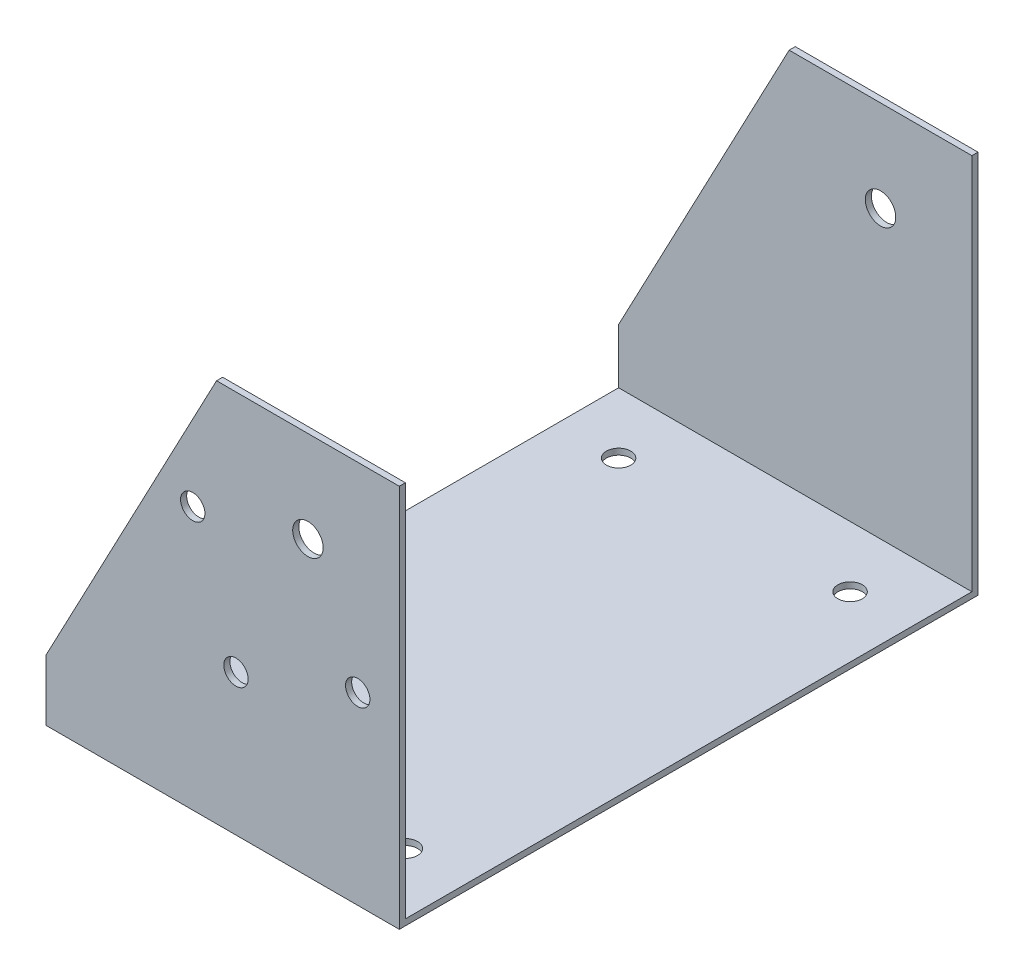
SolidWorks part; units mm, degrees
ref_plane "Alzado" through (0, 0, 0) normal (0, 0, 1) x (1, 0, 0)
ref_plane "Planta" through (0, 0, 0) normal (0, 1, 0) x (1, 0, 0)
ref_plane "Vista lateral" through (0, 0, 0) normal (1, 0, 0) x (0, 0, -1)
sketch "Croquis1" plane through (0, 0, 0) normal (0, 1, 0) x (1, 0, 0)
  line L1 (29, -47.5) -> (-29, -47.5)
  line L2 (29, -47.5) -> (29, 47.5)
  line L3 (29, 47.5) -> (-29, 47.5)
  line L4 (-29, -47.5) -> (-29, 47.5)
  line L5 (29, -47.5) -> (-29, 47.5) construction
  line L6 (29, 47.5) -> (-29, -47.5) construction
  point P0 (0, 0)
extrude "Saliente-Extruir4" add sketch "Croquis1" along normal blind 1
sketch "Croquis3" plane through (0, 0, 47.5) normal (0, 0, 1) x (1, 0, 0)
  line L0 (-29, 1) -> (29, 1)
  line L1 (29, 1) -> (29, 63)
  line L2 (29, 63) -> (-29, 63)
  line L3 (-29, 63) -> (-29, 1)
extrude "Saliente-Extruir5" add sketch "Croquis3" against normal blind 1
sketch "Croquis4" plane through (0, 0, -47.5) normal (0, 0, -1) x (-1, 0, 0)
  line L0 (-29, 1) -> (29, 1)
  line L1 (29, 1) -> (29, 63)
  line L2 (29, 63) -> (29, 1) construction
  line L3 (29, 63) -> (-29, 63)
  line L4 (-29, 63) -> (-29, 1)
extrude "Saliente-Extruir6" add sketch "Croquis4" against normal blind 1
sketch "Croquis6" plane through (0, 0, -47.5) normal (0, 0, -1) x (-1, 0, 0)
  line L0 (29, 0) -> (29, 10) construction
  line L1 (29, 63) -> (29, 0) construction
  line L2 (-29, 63) -> (1, 63) construction
  line L3 (29, 63) -> (-29, 63) construction
  line L4 (1, 63) -> (29, 10)
  line L5 (29, 10) -> (29, 63)
  line L6 (29, 63) -> (1, 63)
extrude "Cortar-Extruir4" cut sketch "Croquis6" against normal blind 1
sketch "Croquis7" plane through (0, 0, 47.5) normal (0, 0, 1) x (1, 0, 0)
  line L0 (-29, 0) -> (-29, 10) construction
  line L1 (-29, 63) -> (-29, 0) construction
  line L2 (29, 63) -> (-1, 63) construction
  line L3 (29, 63) -> (-29, 63) construction
  line L4 (-1, 63) -> (-29, 10)
  line L5 (-29, 10) -> (-29, 63)
  line L6 (-29, 63) -> (-1, 63)
extrude "Cortar-Extruir5" cut sketch "Croquis7" against normal blind 1
sketch "Croquis8" plane through (0, 0, 47.5) normal (0, 0, 1) x (1, 0, 0)
  line L0 (14, 63) -> (14, 48) construction
  line L1 (29, 63) -> (-1, 63) construction
  circle A0 centre (14, 48) radius 2.5
extrude "Cortar-Extruir6" cut sketch "Croquis8" against normal blind 1
sketch "Croquis9" plane through (0, 0, -47.5) normal (0, 0, -1) x (-1, 0, 0)
  line L0 (-14, 63) -> (-14, 48) construction
  line L1 (1, 63) -> (-29, 63) construction
  circle A0 centre (-14, 48) radius 2.5
extrude "Cortar-Extruir7" cut sketch "Croquis9" against normal blind 1
sketch "Croquis10" plane through (0, 0, 47.5) normal (0, 0, 1) x (1, 0, 0)
  line L0 (14, 50.5) -> (14, 35.5) construction
  line L3 (14, 48) -> (8.6295, 36.7125) construction
  line L4 (8.6295, 36.7125) -> (8.6333, 36.7125) construction
  line L7 (14, 48) -> (16.5, 48) construction
  line L8 (14, 48) -> (11.5, 48) construction
  line L9 (8.6295, 36.7125) -> (15.0741, 50.2575) construction
  line L10 (14, 48) -> (15.0741, 50.2575) construction
  line L11 (8.6295, 36.7125) -> (-4.9155, 43.1571) construction
  line L12 (8.6295, 36.7125) -> (8.6333, 36.7125) construction
  line L13 (8.6295, 36.7125) -> (2.1849, 23.1675) construction
  line L14 (-4.9155, 43.1571) -> (22.1745, 30.2679) construction
  line L15 (-4.9155, 43.1571) -> (-4.9102, 43.1571) construction
  circle A0 centre (14, 48) radius 2.5 construction
  circle A1 centre (8.6295, 36.7125) radius 20
  circle A2 centre (8.6295, 36.7125) radius 15
  circle A3 centre (-4.9102, 43.1571) radius 2
  circle A4 centre (2.1849, 23.1675) radius 2
  circle A5 centre (22.1745, 30.2679) radius 2
extrude "Cortar-Extruir8" cut sketch "Croquis10" against normal blind 1 contours A3 | A4 | A5
sketch "Croquis11" plane through (0, 1, 0) normal (0, 1, 0) x (1, 0, 0)
  line L0 (0, 0) -> (-29, 0) construction
  line L1 (-29, 46.5) -> (-29, -46.5) construction
  line L2 (-29, 0) -> (29, 0) construction
  line L3 (29, -46.5) -> (29, 46.5) construction
  line L4 (0, 0) -> (0, 46.5) construction
  line L5 (29, 46.5) -> (-29, 46.5) construction
  line L6 (0, 46.5) -> (0, -46.5) construction
  line L7 (-29, -46.5) -> (29, -46.5) construction
  line L8 (-29, 46.5) -> (-19, 46.5) construction
  line L9 (-19, 46.5) -> (-19, 36.5) construction
  circle A0 centre (-19, 36.5) radius 2
  circle A1 centre (19, 36.5) radius 2
  circle A2 centre (19, -36.5) radius 2
  circle A3 centre (-19, -36.5) radius 2
extrude "Cortar-Extruir9" cut sketch "Croquis11" against normal blind 1
